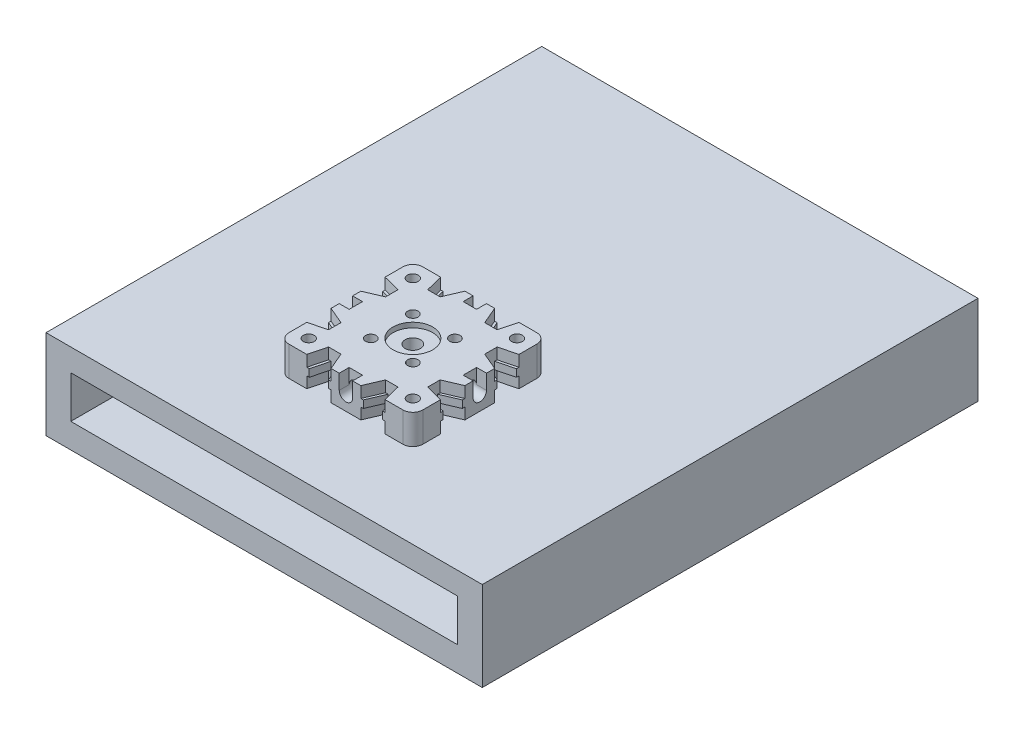
SolidWorks part; units mm, degrees
material "ABS"
ref_plane "正面" through (0, 0, 0) normal (0, 0, 1) x (1, 0, 0)
ref_plane "平面" through (0, 0, 0) normal (0, 1, 0) x (1, 0, 0)
ref_plane "右側面" through (0, 0, 0) normal (1, 0, 0) x (0, 0, -1)
sketch "ｽｹｯﾁ3" plane through (0, 0, 0) normal (0, 1, 0) x (1, 0, 0)
  line L1 (-13.5, 13.5) -> (13.5, 13.5)
  line L2 (-13.5, 13.5) -> (-13.5, -13.5)
  line L3 (-13.5, -13.5) -> (13.5, -13.5)
  line L4 (13.5, 13.5) -> (13.5, -13.5)
  line L5 (-13.5, 13.5) -> (13.5, -13.5) construction
  line L6 (-13.5, -13.5) -> (13.5, 13.5) construction
  point P0 (0, 0)
  dimension "D1" = 27
extrude "ﾎﾞｽ - 押し出し1" add sketch "ｽｹｯﾁ3" along normal mid plane 6
fillet "ﾌｨﾚｯﾄ1" radius 2 4 edges at (-13.5, 0, -13.5) (13.5, 0, -13.5) (-13.5, 0, 13.5) (13.5, 0, 13.5)
sketch "ｽｹｯﾁ4" plane through (0, 3, 0) normal (0, 1, 0) x (1, 0, 0)
  line L1 (-10.5, 10.5) -> (10.5, 10.5) construction
  line L2 (-10.5, 10.5) -> (-10.5, -10.5) construction
  line L3 (-10.5, -10.5) -> (10.5, -10.5) construction
  line L4 (10.5, 10.5) -> (10.5, -10.5) construction
  line L5 (-10.5, 10.5) -> (10.5, -10.5) construction
  line L6 (-10.5, -10.5) -> (10.5, 10.5) construction
  circle A0 centre (-10.5, 10.5) radius 1.1
  circle A1 centre (10.5, 10.5) radius 1.1
  circle A2 centre (-10.5, -10.5) radius 1.1
  circle A3 centre (10.5, -10.5) radius 1.1
  point P0 (0, 0)
  dimension "D6" = 2.2
  dimension "D1" = 21
  dimension "D2" = 21
extrude "ｶｯﾄ - 押し出し1" cut sketch "ｽｹｯﾁ4" against normal blind 6
sketch "ｽｹｯﾁ5" plane through (0, 3, 0) normal (0, 1, 0) x (1, 0, 0)
  circle A0 centre (0, 0) radius 1.55
  dimension "D1" = 3.1
extrude "ｶｯﾄ - 押し出し2" cut sketch "ｽｹｯﾁ5" against normal blind 6
sketch "ｽｹｯﾁ6" plane through (0, 3, 0) normal (0, 1, 0) x (1, 0, 0)
  line L0 (4.2426, 4.2426) -> (0, 0)
  line L1 (0, 0) -> (3.3762, 0)
  circle A0 centre (4.2426, 4.2426) radius 1.05
  dimension "D1" = 2.1
  dimension "D2" = 45
  dimension "D3" = 6
extrude "ｶｯﾄ - 押し出し3" cut sketch "ｽｹｯﾁ6" against normal blind 6
pattern_circular "円形ﾊﾟﾀｰﾝ1" count 4 over 360 about axis through (0, 0, 0) along (0, 1, 0) of "ｶｯﾄ - 押し出し3"
sketch "ｽｹｯﾁ7" plane through (0, 3, 0) normal (0, 1, 0) x (1, 0, 0)
  circle A0 centre (0, 0) radius 4
  dimension "D1" = 8
extrude "ｶｯﾄ - 押し出し4" cut sketch "ｽｹｯﾁ7" against normal blind 1
sketch "ｽｹｯﾁ11" plane through (0, 3, 0) normal (0, 1, 0) x (1, 0, 0)
  line L0 (3, 13.5) -> (4.5, 10)
  line L1 (11.5, 13.5) -> (-11.5, 13.5) construction
  line L2 (4.5, 10) -> (7, 10)
  line L3 (7, 10) -> (7.9, 13.5)
  dimension "D1" = 3.5
  dimension "D2" = 2.5
  dimension "D3" = 7
  dimension "D4" = 3
  dimension "D5" = 7.9
extrude "ｶｯﾄ - 押し出し8" cut sketch "ｽｹｯﾁ11" against normal through all and the other way through all
mirror "ﾐﾗｰ1" about plane through (0, 0, 0) normal (1, 0, 0) of "ｶｯﾄ - 押し出し8"
pattern_circular "円形ﾊﾟﾀｰﾝ2" count 4 over 360 about axis through (0, 0, 0) along (0, 1, 0) of "ｶｯﾄ - 押し出し8", "ﾐﾗｰ1"
sketch "ｽｹｯﾁ12" plane through (0, 0, 13.5) normal (0, 0, 1) x (1, 0, 0)
  circle A0 centre (0, 0) radius 1.35
  dimension "D1" = 2.7
extrude "ｶｯﾄ - 押し出し9" cut sketch "ｽｹｯﾁ12" against normal blind 8
pattern_circular "円形ﾊﾟﾀｰﾝ3" count 4 over 360 about axis through (0, 0, 0) along (0, 1, 0) of "ｶｯﾄ - 押し出し9"
sketch "ｽｹｯﾁ13" plane through (0, 0, 0) normal (0, 1, 0) x (1, 0, 0)
  line L0 (7.9, 13.5) -> (7, 10)
  line L1 (7, 10) -> (6.5, 10)
  line L2 (7, 10) -> (4.5, 10) construction
  line L3 (6.5, 10) -> (7.4, 13.5)
  line L4 (7.4, 13.5) -> (7.9, 13.5)
  line L5 (3, 13.5) -> (3.5, 13.5)
  line L6 (3.5, 13.5) -> (5, 10)
  line L7 (5, 10) -> (4.5, 10)
  line L8 (4.5, 10) -> (3, 13.5)
  dimension "D1" = 0.5
  dimension "D2" = 0.5
extrude "ﾎﾞｽ - 押し出し2" add sketch "ｽｹｯﾁ13" along normal mid plane 1.5
mirror "ﾐﾗｰ2" about plane through (0, 0, 0) normal (1, 0, 0) of "ﾎﾞｽ - 押し出し2"
pattern_circular "円形ﾊﾟﾀｰﾝ4" count 4 over 360 about axis through (0, 0, 0) along (0, 1, 0) of "ﾎﾞｽ - 押し出し2", "ﾐﾗｰ2"
ref_plane "平面1" through (0, 0, -10.5) normal (0, 0, -1) x (-1, 0, 0)
sketch "ｽｹｯﾁ18" plane through (0, 3, 0) normal (0, 1, 0) x (1, 0, 0)
  line L0 (0, 0) -> (6, 0)
  line L1 (0, 0) -> (0, 6)
  dimension "D1" = 6
sketch "ｽｹｯﾁ19" plane through (0, 0, 0) normal (0, 0, 1) x (1, 0, 0)
  line L0 (0, 3) -> (0, 9)
  line L1 (0, 3) -> (6, 3) construction
sketch "ｽｹｯﾁ22" plane through (0, 0, 13.5) normal (0, 0, 1) x (1, 0, 0)
  line L0 (0, 3) -> (6, 3) construction
  line L1 (-1.35, 0) -> (1.35, 0)
  line L2 (-1.35, 0) -> (-1.35, 3)
  line L3 (-1.35, 3) -> (1.35, 3)
  line L4 (1.35, 0) -> (1.35, 3)
  line L5 (-1.35, 0) -> (1.35, 3) construction
  line L6 (-1.35, 3) -> (1.35, 0) construction
  circle A0 centre (0, 0) radius 1.35 construction
  circle A1 centre (0, 0) radius 1.35 construction
  point P4 (0, 1.5)
extrude "ｶｯﾄ - 押し出し15" cut sketch "ｽｹｯﾁ22" against normal blind 2
pattern_circular "円形ﾊﾟﾀｰﾝ11" count 4 over 360 about axis through (0, 0, 0) along (0, 1, 0) of "ｶｯﾄ - 押し出し15"
sketch "ｽｹｯﾁ27" plane through (0, -3, 0) normal (0, -1, 0) x (1, 0, 0)
  line L0 (0, -6) -> (0, 0)
  line L1 (0, 0) -> (-6, 0)
sketch "ｽｹｯﾁ31" plane through (0, -3, 0) normal (0, -1, 0) x (1, 0, 0)
  line L1 (-44, -70) -> (44, -70)
  line L2 (-44, -70) -> (-44, 30)
  line L3 (-44, 30) -> (44, 30)
  line L4 (44, -70) -> (44, 30)
extrude "ﾎﾞｽ - 押し出し4" add sketch "ｽｹｯﾁ31" along normal blind 18
sketch "ｽｹｯﾁ32" plane through (0, 0, 30) normal (0, 0, 1) x (1, 0, 0)
  line L1 (-39, -16) -> (39, -16)
  line L2 (-39, -16) -> (-39, -7.5)
  line L3 (-39, -7.5) -> (39, -7.5)
  line L4 (39, -16) -> (39, -7.5)
extrude "ｶｯﾄ - 押し出し17" cut sketch "ｽｹｯﾁ32" against normal blind 95
